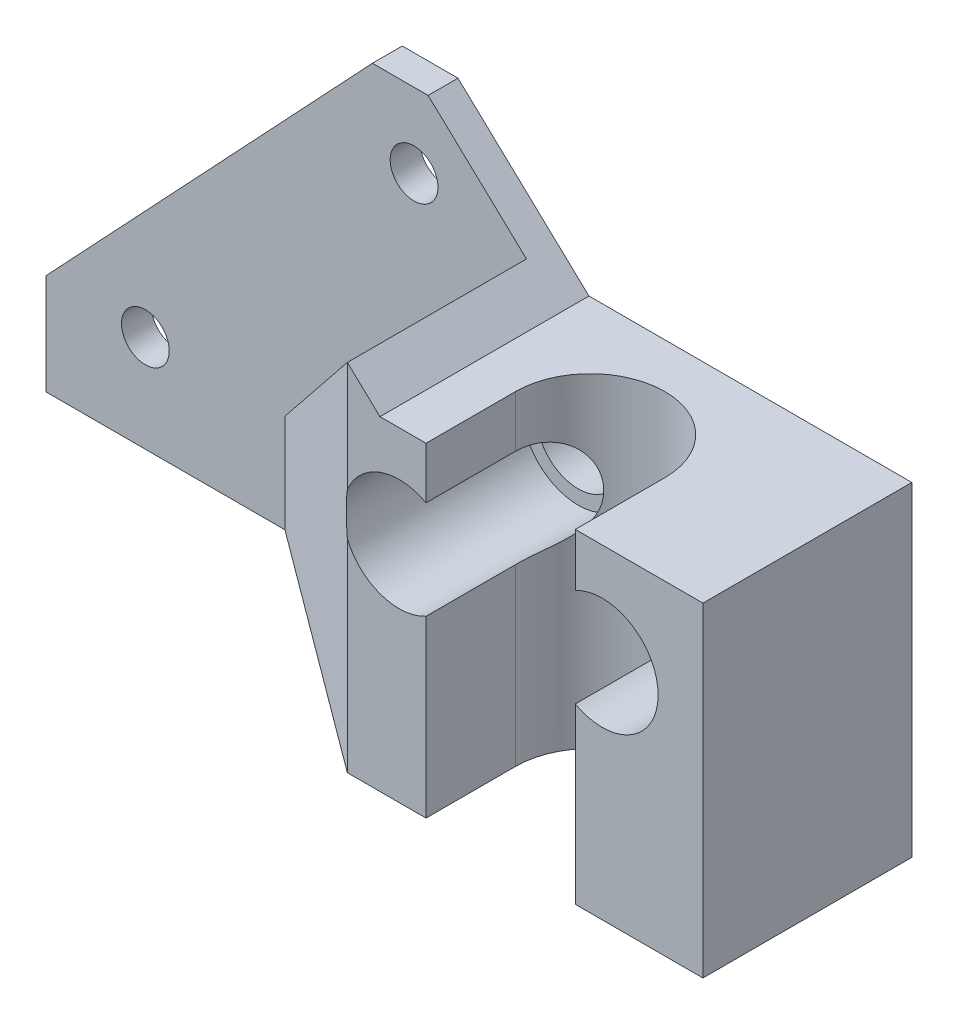
SolidWorks part; units mm, degrees
ref_plane "Front Plane" through (0, 0, 0) normal (0, 0, 1) x (1, 0, 0)
ref_plane "Top Plane" through (0, 0, 0) normal (0, 1, 0) x (1, 0, 0)
ref_plane "Right Plane" through (0, 0, 0) normal (1, 0, 0) x (0, 0, -1)
sketch "Sketch2" plane through (0, 0, 0) normal (0, 0, 1) x (1, 0, 0)
  line L0 (-24.6626, 7.228) -> (-2.8034, 30.4773)
  line L1 (0.9297, 30.4773) -> (9.7043, 22.2273)
  line L2 (9.7043, 22.2273) -> (31.3374, 22.2273)
  line L3 (31.3374, 22.2273) -> (31.3374, 0.4773)
  line L4 (31.3374, 0.4773) -> (-24.6626, 0.4773)
  line L5 (-24.6626, 0.4773) -> (-24.6626, 7.228)
  line L6 (-2.8034, 30.4773) -> (0.9297, 30.4773)
  dimension "D1" = 56
  dimension "D2" = 8.25
  dimension "D3" = 30
extrude "Boss-Extrude1" add sketch "Sketch2" along normal blind 2
sketch "Sketch3" plane through (0, 0, 2) normal (0, 0, 1) x (1, 0, 0)
  line L0 (31.3374, 22.2273) -> (9.7043, 22.2273) construction
  line L1 (31.3374, 0.4773) -> (31.3374, 22.2273) construction
  circle A0 centre (-0.0123, 25.4773) radius 1.6
  circle A1 centre (-18.0123, 6.9773) radius 1.6
  circle A2 centre (10.9877, 15.4773) radius 2.8
  circle A3 centre (24.5874, 15.3914) radius 2.8
  dimension "D1" = 13.6
  dimension "D2" = 3.2
  dimension "D3" = 5.6
  dimension "D4" = 18
  dimension "D9" = 6.75
  dimension "D5" = 18.5
  dimension "D6" = 11
  dimension "D7" = 10
  dimension "D8" = 6.75
extrude "Cut-Extrude1" cut sketch "Sketch3" against normal blind 2
sketch "Sketch5" plane through (0, 0, 2) normal (0, 0, 1) x (1, 0, 0)
  line L0 (-8.6626, 7.072) -> (7.5187, 24.2823)
  line L2 (7.5187, 24.2823) -> (9.7043, 22.2273)
  line L4 (-2.8034, 30.4773) -> (-24.6626, 7.228) construction
  line L5 (9.7043, 22.2273) -> (0.9297, 30.4773) construction
  line L6 (-24.6626, 0.4773) -> (31.3374, 0.4773) construction
  line L11 (31.3374, 22.2273) -> (31.3374, 3.4773)
  line L12 (31.3374, 0.4773) -> (31.3374, 22.2273) construction
  line L13 (-8.6626, 7.072) -> (-8.6626, 0.4773)
  line L18 (-8.6626, 0.4773) -> (31.3374, 0.4773)
  line L19 (31.3374, 0.4773) -> (31.3374, 3.4773)
  line L21 (9.7043, 22.2273) -> (31.3374, 22.2273)
  circle A0 centre (10.9877, 15.4773) radius 3.75
  circle A1 centre (24.5874, 15.3914) radius 3.75
  point P16 (-8.6626, 3.7747)
  dimension "D1" = 7.5
  dimension "D2" = 3
  dimension "D3" = 40
extrude "Boss-Extrude2" add sketch "Sketch5" along normal blind 12
sketch "Sketch6" plane through (0, 0, 0) normal (0, 0, -1) x (-1, 0, 0)
  line L0 (-17.7873, 0.4773) -> (-17.7873, 22.2273) construction
  line L1 (24.6626, 0.4773) -> (-31.3374, 0.4773) construction
  line L2 (-31.3374, 22.2273) -> (-9.7043, 22.2273) construction
  line L3 (-24.5874, 15.3914) -> (-17.7873, 15.3914) construction
  line L4 (-17.7873, 15.3914) -> (-10.9877, 15.4773) construction
sketch "Sketch7" plane through (0, 22.2273, 0) normal (0, 1, 0) x (1, 0, 0)
  line L0 (17.7873, 0) -> (17.7873, -14) construction
  line L1 (17.7873, 0) -> (10.9877, 0) construction
  line L2 (24.5874, 0) -> (17.7873, 0) construction
  line L3 (31.3374, -14) -> (9.7043, -14) construction
sketch "Sketch10" plane through (0, 22.2273, 0) normal (0, 1, 0) x (1, 0, 0)
  line L0 (17.7873, -14) -> (17.7873, -8) construction
  line L1 (17.7873, 0) -> (17.7873, -14) construction
  line L2 (12.7873, -14) -> (12.7873, -8)
  line L3 (22.7873, -14) -> (22.7873, -8)
  line L6 (7.5187, -2) -> (31.3374, -2) construction
  line L7 (31.3374, -14) -> (31.3374, 0) construction
  line L8 (17.7873, -2) -> (17.7873, -8) construction
  arc A0 (12.7873, -14) -> (22.7873, -14) centre (17.7873, -14) ccw
  arc A1 (22.7873, -8) -> (12.7873, -8) centre (17.7873, -8) ccw
  point P5 (17.7873, -11)
  dimension "D1" = 5
extrude "Cut-Extrude2" cut sketch "Sketch10" against normal through all
sketch "Sketch11" plane through (0, 22.2273, 0) normal (0, 1, 0) x (1, 0, 0)
  line L0 (-8.6626, -2) -> (7.5187, -14)
  line L1 (7.5187, -14) -> (-8.6626, -14) construction
  line L2 (7.5187, -14) -> (-8.6626, -14)
  line L3 (-8.6626, -14) -> (-8.6626, -2)
extrude "Cut-Extrude3" cut sketch "Sketch11" against normal through all both and the other way through all
